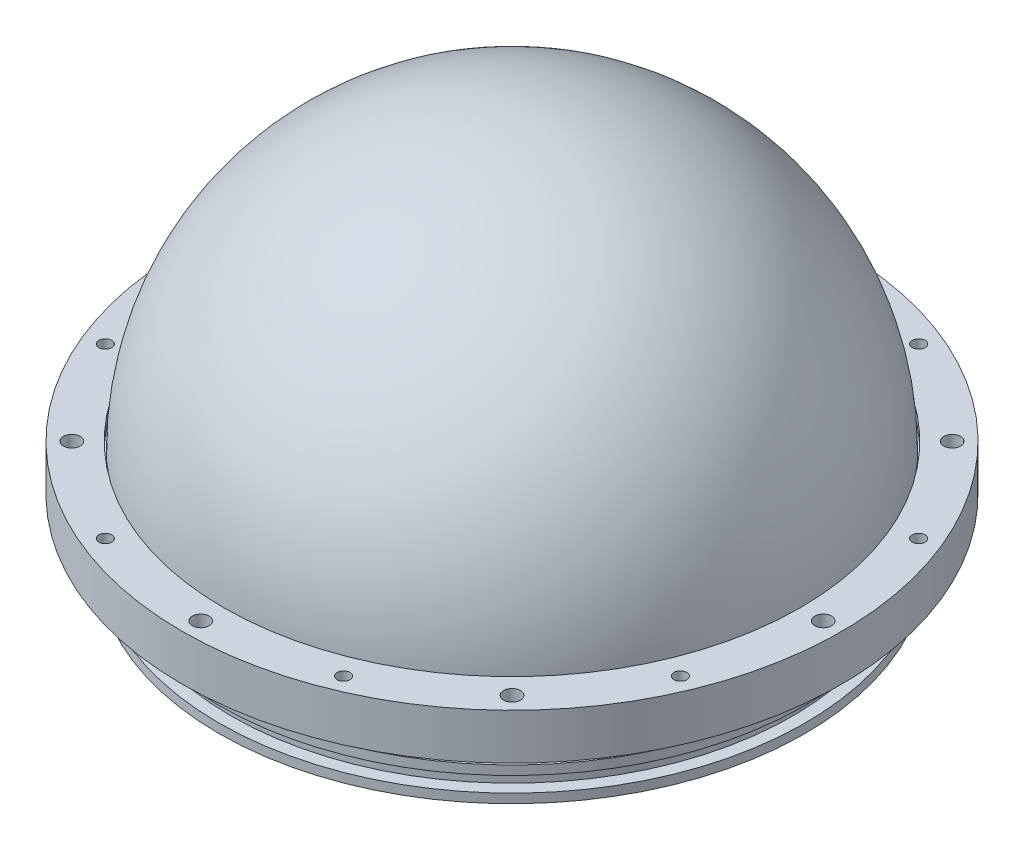
SolidWorks part; units mm, degrees
material "6061-T6"
ref_plane "Front" through (0, 0, 0) normal (0, 0, 1) x (1, 0, 0)
ref_plane "Top" through (0, 0, 0) normal (0, 1, 0) x (1, 0, 0)
ref_plane "Right" through (0, 0, 0) normal (1, 0, 0) x (0, 0, -1)
sketch "Sketch1" plane through (0, 0, 0) normal (0, 0, 1) x (1, 0, 0)
  line L0 (0, 17.5) -> (0, -17.5) construction
  line L1 (78.5, -17.5) -> (78.5, 2.5)
  line L2 (78.5, 2.5) -> (73.5, 2.5)
  line L3 (73.5, 2.5) -> (73.5, 6.5)
  line L4 (73.5, 6.5) -> (78.5, 6.5)
  line L5 (78.5, 6.5) -> (78.5, 14.5)
  line L6 (78.5, 14.5) -> (94.5, 14.5)
  line L7 (94.5, 14.5) -> (94.5, 17.5)
  line L8 (94.5, 17.5) -> (108, 17.5)
  line L9 (108, 17.5) -> (108, 2.5)
  line L11 (96, 2.5) -> (96, -1.5)
  line L12 (96, -17.5) -> (78.5, -17.5)
  line L13 (96, 2.5) -> (108, 2.5)
  line L14 (96, -1.5) -> (92, -1.5)
  line L15 (92, -1.5) -> (92, -6.5)
  line L16 (92, -6.5) -> (96, -6.5)
  line L17 (96, -9.5) -> (92, -9.5)
  line L18 (92, -9.5) -> (92, -14.5)
  line L19 (92, -14.5) -> (96, -14.5)
  line L20 (96, -6.5) -> (96, -9.5)
  line L21 (96, -14.5) -> (96, -17.5)
  dimension "D1" = 157
  dimension "D2" = 20
  dimension "D3" = 147
  dimension "D4" = 189
  dimension "D5" = 35
  dimension "D6" = 216
  dimension "D7" = 20
  dimension "D8" = 192
  dimension "D9" = 4
  dimension "D10" = 3
  dimension "D11" = 5
  dimension "D12" = 3
  dimension "D13" = 3
  dimension "D14" = 4
revolve "Revolve1" add sketch "Sketch1" angle 360 about L0
hole_wizard "Ø5.5 (5.5) Diameter Hole1" positions "Sketch2" profile "Sketch3" hole size "Ø5.5" standard "ANSI Metric" end condition up to next
sketch "Sketch2" plane through (0, 17.5, 0) normal (0, 1, 0) x (1, 0, 0)
  line L0 (102, 0) -> (-102, 0) construction
  point P0 (102, 0)
  point P6 (72.1249, -72.1249)
  point P7 (0, -102)
  point P8 (-72.1249, -72.1249)
  point P9 (-102, 0)
  point P10 (-72.1249, 72.1249)
  point P11 (0, 102)
  point P12 (72.1249, 72.1249)
  dimension "D2" = 204
  dimension "D1" = 8
sketch "Sketch3" plane through (102, 17.5, 0) normal (1, 0, 0) x (0, 0, 1)
  line L0 (0, 0) -> (0, 15)
  line L1 (0, 15) -> (2.75, 15)
  line L2 (2.75, 15) -> (2.75, 0)
  line L5 (2.75, 0) -> (0, 0)
  line L11 (0, -6.35) -> (0, 107.95) construction
  dimension "Thru Hole Dia." = 5.5
  dimension "Thru Hole Depth" = 15
hole_wizard "M5x0.8 Tapped Hole1" positions "Sketch4" profile "Sketch5" tap size "M5x0.8" standard "ANSI Metric" end condition up to next
sketch "Sketch4" plane through (0, 17.5, 0) normal (0, 1, 0) x (1, 0, 0)
  line L0 (94.2357, 39.0337) -> (-94.2357, -39.0337) construction
  line L2 (102, 0) -> (-102, 0) construction
  point P0 (94.2357, 39.0337)
  point P7 (94.2357, -39.0337)
  point P8 (39.0337, -94.2357)
  point P9 (-39.0337, -94.2357)
  point P10 (-94.2357, -39.0337)
  point P11 (-94.2357, 39.0337)
  point P12 (-39.0337, 94.2357)
  point P13 (39.0337, 94.2357)
  dimension "D2" = 22.5
  dimension "D1" = 8
sketch "Sketch5" plane through (94.2357, 17.5, -39.0337) normal (1, 0, 0) x (0, 0, 1)
  line L0 (0, 0) -> (0, 15)
  line L1 (0, 15) -> (2.1, 15)
  line L2 (2.1, 15) -> (2.1, 0)
  line L5 (2.1, 0) -> (0, 0)
  line L11 (0, -6.35) -> (0, 107.95) construction
  dimension "Thru Tap Drill Dia." = 4.2
  dimension "Thru Tap Drill Depth" = 15
cosmetic thread "Hole Thread1" parameters "D2"=5
cosmetic thread "Hole Thread2" parameters "D2"=5
cosmetic thread "Hole Thread3" parameters "D2"=5
cosmetic thread "Hole Thread4" parameters "D2"=5
cosmetic thread "Hole Thread5" parameters "D2"=5
cosmetic thread "Hole Thread6" parameters "D2"=5
cosmetic thread "Hole Thread7" parameters "D2"=5
cosmetic thread "Hole Thread8" parameters "D2"=5
sketch "Sketch6" plane through (0, 0, 0) normal (0, 0, 1) x (1, 0, 0)
  line L0 (0, 108.5) -> (0, 14.5) construction
  line L1 (78.5, 14.5) -> (94.5, 14.5) construction
  line L2 (87.65, 14.5) -> (94, 14.5)
  line L3 (0, 108.5) -> (0, 102.15)
  arc A0 (0, 108.5) -> (94, 14.5) centre (0, 14.5) cw
  arc A1 (0, 102.15) -> (87.65, 14.5) centre (0, 14.5) cw
  dimension "D1" = 94
  dimension "D2" = 6.35
revolve "Revolve2" add sketch "Sketch6" angle 360 about L0
